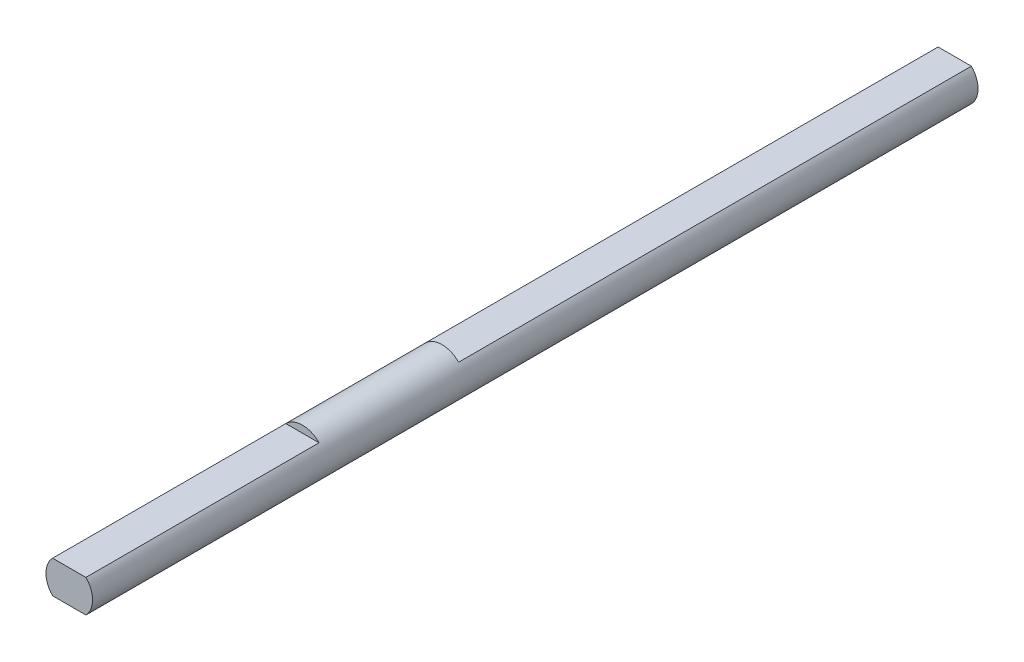
SolidWorks part; units mm, degrees
ref_plane "Plano frontal" through (0, 0, 0) normal (0, 0, 1) x (1, 0, 0)
ref_plane "Plano superior" through (0, 0, 0) normal (0, 1, 0) x (1, 0, 0)
ref_plane "Plano direito" through (0, 0, 0) normal (1, 0, 0) x (0, 0, -1)
sketch "Esboço1" plane through (0, 0, 0) normal (0, 0, 1) x (1, 0, 0)
  circle A0 centre (0, 0) radius 2.5
  dimension "D1" = 5
extrude "Ressalto-extrusão1" add sketch "Esboço1" along normal blind 65 and the other way blind 30
sketch "Esboço5" plane through (0, 0, 65) normal (0, 0, 1) x (1, 0, 0)
  line L1 (0, 1.75) -> (2.6915, 1.75)
  line L2 (2.6915, 1.75) -> (2.6915, 3.0794)
  line L3 (2.6915, 3.0794) -> (-3.6726, 3.0794)
  line L4 (-3.6726, 3.0794) -> (-3.6726, 1.75)
  line L5 (-3.6726, 1.75) -> (0, 1.75)
  line L6 (0, -1.75) -> (2.6915, -1.75)
  line L7 (2.6915, -1.75) -> (2.6915, -3.18)
  line L8 (2.6915, -3.18) -> (-3.6726, -3.18)
  line L9 (-3.6726, -3.18) -> (-3.6726, -1.75)
  line L10 (-3.6726, -1.75) -> (0, -1.75)
  point P5 (0, 0)
  dimension "D1" = 3.5
  dimension "D2" = 1.75
extrude "Corte-extrusão4" cut sketch "Esboço5" against normal blind 25.015
sketch "Esboço6" plane through (0, 0, -30) normal (0, 0, -1) x (-1, 0, 0)
  line L0 (0, 1.75) -> (0, -1.75) construction
  line L1 (0, 1.75) -> (2.6412, 1.75)
  line L2 (2.6412, 1.75) -> (2.6412, 2.9138)
  line L3 (2.6412, 2.9138) -> (-2.8718, 2.9138)
  line L4 (-2.8718, 2.9138) -> (-2.8718, 1.75)
  line L5 (-2.8718, 1.75) -> (0, 1.75)
  line L6 (0, -1.75) -> (2.6412, -1.75)
  line L7 (2.6412, -1.75) -> (2.6412, -3.0186)
  line L8 (2.6412, -3.0186) -> (-2.8718, -3.0186)
  line L9 (-2.8718, -3.0186) -> (-2.8718, -1.75)
  line L10 (-2.8718, -1.75) -> (0, -1.75)
  point P5 (0, 0)
  dimension "D1" = 3.5
extrude "Corte-extrusão5" cut sketch "Esboço6" against normal blind 55.015
